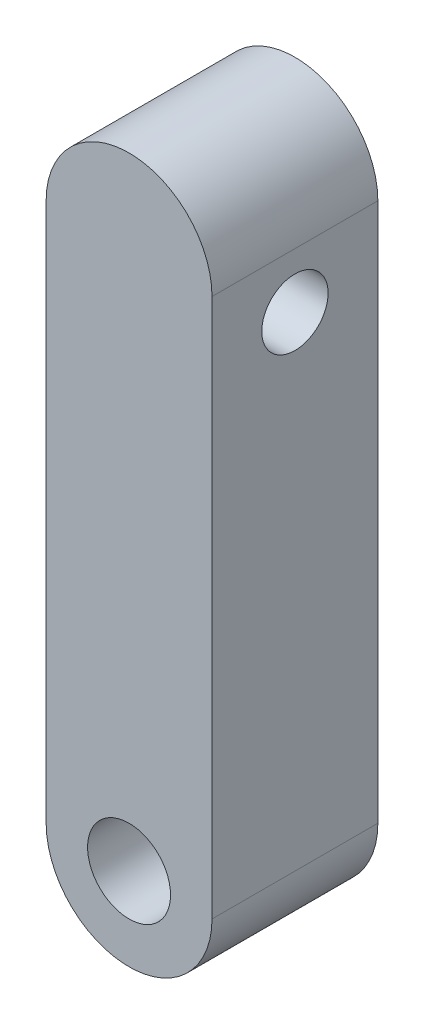
SolidWorks part; units mm, degrees
ref_plane "Front Plane" through (0, 0, 0) normal (0, 0, 1) x (1, 0, 0)
ref_plane "Top Plane" through (0, 0, 0) normal (0, 1, 0) x (1, 0, 0)
ref_plane "Right Plane" through (0, 0, 0) normal (1, 0, 0) x (0, 0, -1)
sketch "Sketch2" plane through (0, 0, 0) normal (0, 0, 1) x (1, 0, 0)
  line L0 (0, 0) -> (0, 65) construction
  line L1 (-10, 0) -> (-10, 65)
  line L2 (10, 0) -> (10, 65)
  arc A0 (-10, 0) -> (10, 0) centre (0, 0) ccw
  arc A1 (10, 65) -> (-10, 65) centre (0, 65) ccw
  circle A2 centre (0, 0) radius 5
  point P2 (0, 32.5)
  dimension "D1" = 20
  dimension "D2" = 65
extrude "Boss-Extrude1" add sketch "Sketch2" along normal blind 20
sketch "Sketch4" plane through (10, 0, 0) normal (1, 0, 0) x (0, 0, -1)
  line L0 (-10, 65) -> (-10, 58.36) construction
  line L1 (-20, 65) -> (0, 65) construction
  circle A0 centre (-10, 58.36) radius 4
  dimension "D1" = 6.64
extrude "Cut-Extrude1" cut sketch "Sketch4" against normal blind 55
ref_plane "Plane1" through (0, 0, 10) normal (0, 0, 1) x (1, 0, 0)
sketch "Sketch5" plane through (0, 0, 10) normal (0, 0, 1) x (1, 0, 0)
  line L0 (0, 0) -> (0, 16.3616) construction
  line L1 (0, 0) -> (-17.8535, 0) construction
  point P4 (0, 0)
